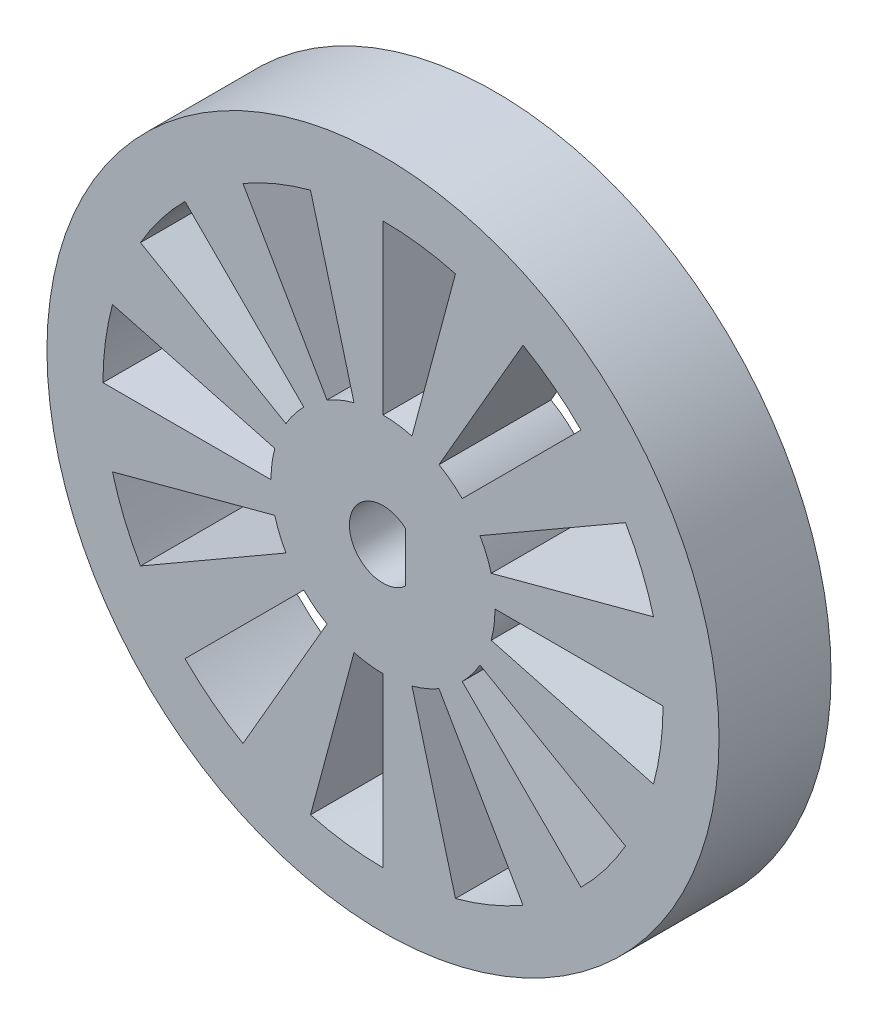
SolidWorks part; units mm, degrees
ref_plane "前基準面" through (0, 0, 0) normal (0, 0, 1) x (1, 0, 0)
ref_plane "上基準面" through (0, 0, 0) normal (0, 1, 0) x (1, 0, 0)
ref_plane "右基準面" through (0, 0, 0) normal (1, 0, 0) x (0, 0, -1)
sketch "草圖2" plane through (0, 0, 0) normal (0, 0, 1) x (1, 0, 0)
  line L0 (0, 5) -> (0, 12.5)
  line L1 (1.2941, 4.8296) -> (3.2352, 12.0741)
  line L2 (2.5, 4.3301) -> (6.25, 10.8253)
  line L3 (3.5355, 3.5355) -> (8.8388, 8.8388)
  line L4 (4.3301, 2.5) -> (10.8253, 6.25)
  line L5 (4.8296, 1.2941) -> (12.0741, 3.2352)
  line L6 (5, 0) -> (12.5, 0)
  line L7 (4.8296, -1.2941) -> (12.0741, -3.2352)
  line L8 (4.3301, -2.5) -> (10.8253, -6.25)
  line L9 (3.5355, -3.5355) -> (8.8388, -8.8388)
  line L10 (2.5, -4.3301) -> (6.25, -10.8253)
  line L11 (1.2941, -4.8296) -> (3.2352, -12.0741)
  line L12 (0, -5) -> (0, -12.5)
  line L13 (-1.2941, -4.8296) -> (-3.2352, -12.0741)
  line L14 (-2.5, -4.3301) -> (-6.25, -10.8253)
  line L15 (-3.5355, -3.5355) -> (-8.8388, -8.8388)
  line L16 (-4.3301, -2.5) -> (-10.8253, -6.25)
  line L17 (-4.8296, -1.2941) -> (-12.0741, -3.2352)
  line L18 (-5, 0) -> (-12.5, 0)
  line L19 (-4.8296, 1.2941) -> (-12.0741, 3.2352)
  line L20 (-4.3301, 2.5) -> (-10.8253, 6.25)
  line L21 (-3.5355, 3.5355) -> (-8.8388, 8.8388)
  line L22 (-2.5, 4.3301) -> (-6.25, 10.8253)
  line L23 (-1.2941, 4.8296) -> (-3.2352, 12.0741)
  line L24 (1, -1.118) -> (1, 1.118)
  circle A0 centre (0, 0) radius 15
  arc A1 (-3.2352, 12.0741) -> (-6.25, 10.8253) centre (0, 0) ccw
  arc A2 (-1.2941, 4.8296) -> (-2.5, 4.3301) centre (0, 0) ccw
  arc A3 (-3.5355, 3.5355) -> (-4.3301, 2.5) centre (0, 0) ccw
  arc A4 (-8.8388, 8.8388) -> (-10.8253, 6.25) centre (0, 0) ccw
  arc A5 (-12.0741, 3.2352) -> (-12.5, 0) centre (0, 0) ccw
  arc A6 (-4.8296, 1.2941) -> (-5, 0) centre (0, 0) ccw
  arc A7 (-12.0741, -3.2352) -> (-10.8253, -6.25) centre (0, 0) ccw
  arc A8 (-4.8296, -1.2941) -> (-4.3301, -2.5) centre (0, 0) ccw
  arc A9 (-3.5355, -3.5355) -> (-2.5, -4.3301) centre (0, 0) ccw
  arc A10 (-8.8388, -8.8388) -> (-6.25, -10.8253) centre (0, 0) ccw
  arc A11 (-3.2352, -12.0741) -> (0, -12.5) centre (0, 0) ccw
  arc A12 (-1.2941, -4.8296) -> (0, -5) centre (0, 0) ccw
  arc A13 (1.2941, -4.8296) -> (2.5, -4.3301) centre (0, 0) ccw
  arc A14 (3.2352, -12.0741) -> (6.25, -10.8253) centre (0, 0) ccw
  arc A15 (8.8388, -8.8388) -> (10.8253, -6.25) centre (0, 0) ccw
  arc A16 (3.5355, -3.5355) -> (4.3301, -2.5) centre (0, 0) ccw
  arc A17 (4.8296, -1.2941) -> (5, 0) centre (0, 0) ccw
  arc A18 (4.8296, 1.2941) -> (4.3301, 2.5) centre (0, 0) ccw
  arc A19 (3.5355, 3.5355) -> (2.5, 4.3301) centre (0, 0) ccw
  arc A20 (1.2941, 4.8296) -> (0, 5) centre (0, 0) ccw
  arc A21 (3.2352, 12.0741) -> (0, 12.5) centre (0, 0) ccw
  arc A22 (8.8388, 8.8388) -> (6.25, 10.8253) centre (0, 0) ccw
  arc A23 (12.0741, 3.2352) -> (10.8253, 6.25) centre (0, 0) ccw
  arc A24 (12.0741, -3.2352) -> (12.5, 0) centre (0, 0) ccw
  arc A25 (1, 1.118) -> (1, -1.118) centre (0, 0) ccw
  point P55 (0, 0)
  dimension "D1" = 30
  dimension "D2" = 25
  dimension "D3" = 10
  dimension "D5" = 3
  dimension "D6" = 1
  dimension "D4" = 24
extrude "填料-伸長1" add sketch "草圖2" along normal blind 5
